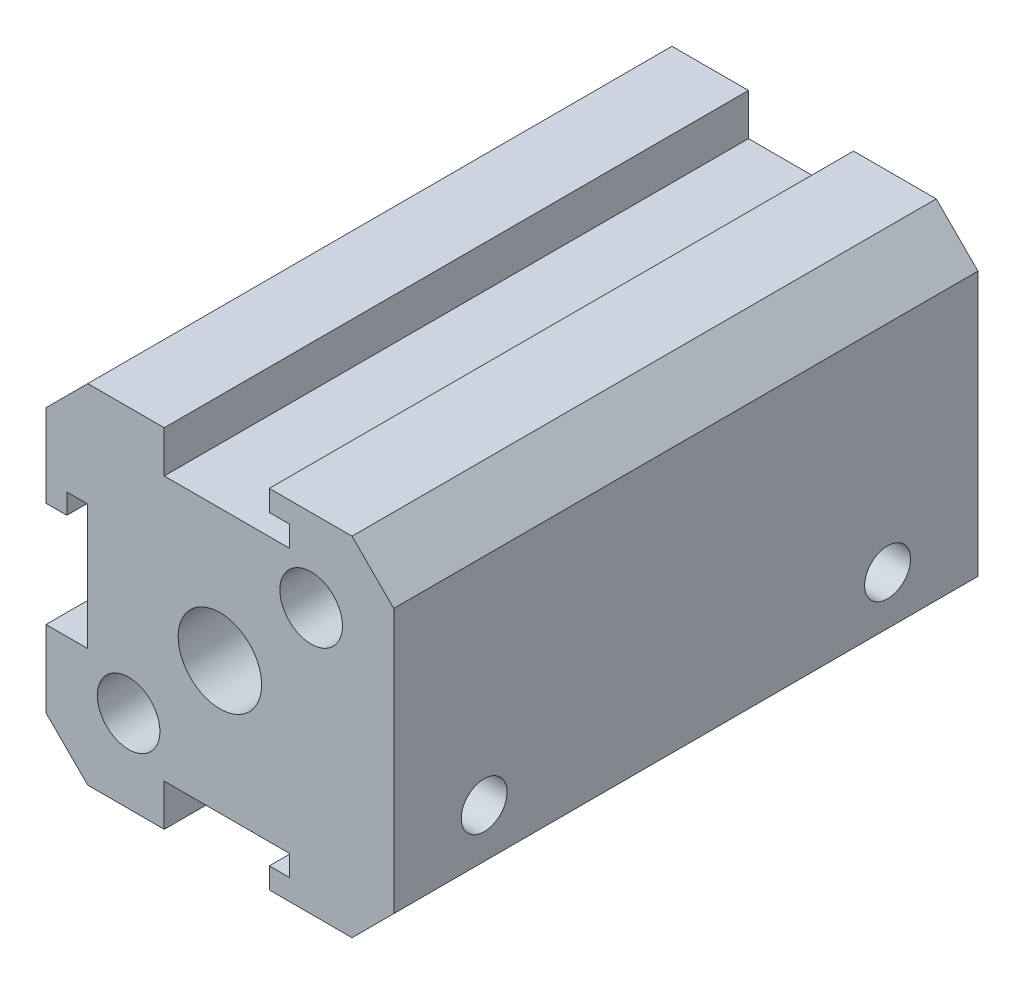
SolidWorks part; units mm, degrees
ref_plane "Front Plane" through (0, 0, 0) normal (0, 0, 1) x (1, 0, 0)
ref_plane "Top Plane" through (0, 0, 0) normal (0, 1, 0) x (1, 0, 0)
ref_plane "Right Plane" through (0, 0, 0) normal (1, 0, 0) x (0, 0, -1)
sketch "Sketch1" plane through (0, 0, 0) normal (0, 0, 1) x (1, 0, 0)
  line L0 (-12.5, -9.5) -> (-9.5, -12.5)
  line L1 (-9.5, -12.5) -> (-4, -12.5)
  line L2 (-12.5, -9.5) -> (-12.5, -4)
  line L3 (-9.5, 12.5) -> (-4, 12.5)
  line L4 (12.5, -9.5) -> (12.5, 9.5)
  line L5 (-12.5, -12.5) -> (12.5, 12.5) construction
  line L6 (-12.5, 12.5) -> (12.5, -12.5) construction
  line L7 (-4, -12.5) -> (-4, -9.5)
  line L8 (-4, -9.5) -> (5, -9.5)
  line L9 (5, -9.5) -> (5, -11)
  line L10 (5, -11) -> (3.55, -11)
  line L11 (3.55, -11) -> (3.55, -12.5)
  line L12 (9.5, -12.5) -> (12.5, -9.5)
  line L13 (12.5, 9.5) -> (9.5, 12.5)
  line L14 (-9.5, 12.5) -> (-12.5, 9.5)
  line L15 (-4, 12.5) -> (-4, 9.5)
  line L16 (-4, 9.5) -> (5, 9.5)
  line L17 (5, 9.5) -> (5, 11)
  line L18 (5, 11) -> (3.55, 11)
  line L19 (3.55, 11) -> (3.55, 12.5)
  line L20 (-12.5, -4) -> (-9.5, -4)
  line L21 (-9.5, -4) -> (-9.5, 5)
  line L22 (-9.5, 5) -> (-11, 5)
  line L23 (-11, 5) -> (-11, 3.55)
  line L24 (-11, 3.55) -> (-12.5, 3.55)
  line L25 (-12.5, 3.55) -> (-12.5, 9.5)
  line L26 (3.55, 12.5) -> (9.5, 12.5)
  line L27 (3.55, -12.5) -> (9.5, -12.5)
  circle A0 centre (0, 0) radius 3
  point P0 (0, 0)
  dimension "D8" = 6
  dimension "D1" = 25
  dimension "D2" = 25
  dimension "D3" = 7.55
  dimension "D4" = 9
  dimension "D5" = 3
  dimension "D6" = 5.5
  dimension "D7" = 1.5
extrude "Boss-Extrude1" add sketch "Sketch1" along normal blind 42
hole_wizard "M4 Clearance Hole1" positions "Sketch3" profile "Sketch4" hole size "M4" standard "ANSI Metric" end condition through all
sketch "Sketch3" plane through (0, 0, 42) normal (0, 0, 1) x (1, 0, 0)
  line L1 (-9.5, 12.5) -> (-13.3484, 12.5) construction
  line L4 (-12.5, 9.5) -> (-12.5, 12.5) construction
  line L7 (9.5, 12.5) -> (13.6863, 12.5) construction
  line L10 (12.5, 9.5) -> (12.5, 12.5) construction
  line L11 (12.5, 9.5) -> (9.5, 12.5) construction
  line L14 (12.5, -9.5) -> (12.5, -13.8342) construction
  line L17 (9.5, -12.5) -> (12.5, -12.5) construction
  line L20 (-9.5, -12.5) -> (-13.7286, -12.5) construction
  line L23 (-12.5, -9.5) -> (-12.5, -12.5) construction
  line L27 (-12.5, 12.5) -> (12.5, -12.5) construction
  line L28 (-11, -11) -> (-2.1213, -2.1213) construction
  line L29 (-12.5, -9.5) -> (-9.5, -12.5) construction
  line L32 (11, 11) -> (2.1213, 2.1213) construction
  line L34 (-12.5, -12.5) -> (12.5, 12.5) construction
  circle A0 centre (0, 0) radius 3 construction
  point P59 (6.5607, 6.5607)
  point P61 (-6.5607, -6.5607)
sketch "Sketch4" plane through (6.5607, 6.5607, 42) normal (1, 0, 0) x (0, -1, 0)
  line L0 (0, 0) -> (0, 42)
  line L1 (0, 42) -> (2.25, 42)
  line L2 (2.25, 42) -> (2.25, 0)
  line L5 (2.25, 0) -> (0, 0)
  line L11 (0, -6.35) -> (0, 107.95) construction
  dimension "Thru Hole Dia." = 4.5
  dimension "Thru Hole Depth" = 42
hole_wizard "Tap Drill for M4x0.7 Tap1" positions "Sketch7" profile "Sketch6" hole size "M4x0.7" standard "ANSI Metric"
sketch "Sketch7" plane through (12.5, 0, 0) normal (1, 0, 0) x (0, 0, -1)
  line L0 (-42, -6) -> (0, -6) construction
  line L1 (-42, -9.5) -> (-42, 9.5) construction
  line L2 (0, -9.5) -> (0, 9.5) construction
  line L4 (-42, -12.5) -> (0, -12.5) construction
  point P0 (-35.5, -6)
  point P2 (-6.5, -6)
  dimension "D1" = 6.5
  dimension "D2" = 6.5
  dimension "D3" = 6.5
sketch "Sketch6" plane through (12.5, -6, 35.5) normal (0, 1, 0) x (0, 0, -1)
  line L0 (0, 0) -> (0, 6.0714)
  line L1 (0, 6.0714) -> (1.65, 5.08)
  line L2 (1.65, 5.08) -> (1.65, 0)
  line L5 (1.65, 0) -> (0, 0)
  line L10 (0, 6.0714) -> (-1.65, 5.08) construction
  line L11 (0, -6.35) -> (0, 107.95) construction
  dimension "Hole Dia." = 3.3
  dimension "Hole Depth" = 5.08
  dimension "Drill Angle" = 118
equation "\"D1@Sketch1\"=\"D2@Sketch1\""
